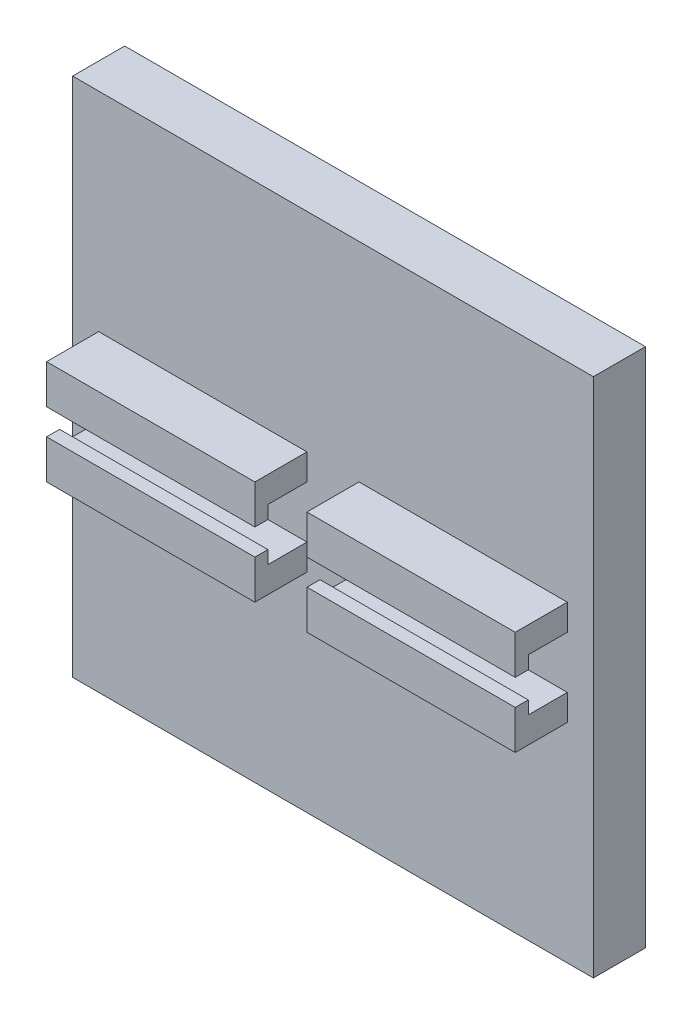
SolidWorks part; units mm, degrees
ref_plane "Front Plane" through (0, 0, 0) normal (0, 0, 1) x (1, 0, 0)
ref_plane "Top Plane" through (0, 0, 0) normal (0, 1, 0) x (1, 0, 0)
ref_plane "Right Plane" through (0, 0, 0) normal (1, 0, 0) x (0, 0, -1)
sketch "Sketch1" plane through (0, 0, 0) normal (0, 0, 1) x (1, 0, 0)
  line L1 (-50, 50) -> (50, 50)
  line L2 (-50, 50) -> (-50, -50)
  line L3 (-50, -50) -> (50, -50)
  line L4 (50, 50) -> (50, -50)
  line L5 (-50, 50) -> (50, -50) construction
  line L6 (-50, -50) -> (50, 50) construction
  point P0 (0, 0)
  dimension "D1" = 100
  dimension "D2" = 100
extrude "back plate" add sketch "Sketch1" along normal blind 10
sketch "Sketch2" plane through (0, 0, 10) normal (0, 0, 1) x (1, 0, 0)
  line L0 (-25, 0) -> (-25, 50) construction
  line L1 (-50, 50) -> (-50, -50) construction
  line L3 (-50, 0) -> (0, 0) construction
  line L4 (-45, 10) -> (-5, 10)
  line L5 (-45, 10) -> (-45, -10)
  line L6 (-45, -10) -> (-5, -10)
  line L7 (-5, 10) -> (-5, -10)
  line L8 (-45, 10) -> (-5, -10) construction
  line L9 (-45, -10) -> (-5, 10) construction
  line L12 (50, 50) -> (-50, 50) construction
  point P6 (-25, 0)
  point P12 (-25, 0)
  point P13 (0, 0)
  point P15 (0, 0)
  point P16 (0, 0)
  point P17 (0, 0)
  point P18 (-25, 0)
  point P19 (-40.8147, 8.9771)
  dimension "D1" = 20
  dimension "D2" = 40
extrude "slider mount boss" add sketch "Sketch2" along normal blind 10
sketch "Sketch3" plane through (-5, 0, 0) normal (1, 0, 0) x (0, 0, -1)
  line L0 (-10, -10) -> (-10, 10) construction
  line L1 (-17.5, 5) -> (-10, 5)
  line L2 (-17.5, 5) -> (-17.5, 2.5)
  line L3 (-17.5, -5) -> (-10, -5)
  line L4 (-10, 5) -> (-10, -5)
  line L5 (-17.5, 5) -> (-10, -5) construction
  line L6 (-17.5, -5) -> (-10, 5) construction
  line L7 (-17.5, -2.5) -> (-17.5, -5)
  line L8 (-20, 2.5) -> (-17.5, 2.5)
  line L9 (-20, 2.5) -> (-20, -2.5)
  line L10 (-20, -2.5) -> (-17.5, -2.5)
  line L12 (-20, 2.5) -> (-17.5, -2.5) construction
  line L13 (-20, -2.5) -> (-17.5, 2.5) construction
  point P4 (-13.75, 0)
  point P6 (-10, 0)
  point P12 (-18.75, 0)
  point P13 (-24.3575, -0.3264)
  point P14 (-17.5, 0)
  point P15 (-17.5, 1.7123)
  point P16 (0, 0)
  point P17 (-18.75, 0)
  point P18 (-13.75, 0)
  point P19 (-18.75, 0)
  point P20 (-18.75, 0)
  dimension "D1" = 7.5
  dimension "D2" = 10
  dimension "D3" = 5
  dimension "D4" = 2.5
extrude "slider mount" cut sketch "Sketch3" against normal through all
mirror "Mirror3" about plane through (0, 0, 0) normal (1, 0, 0) of "slider mount", "slider mount boss"
